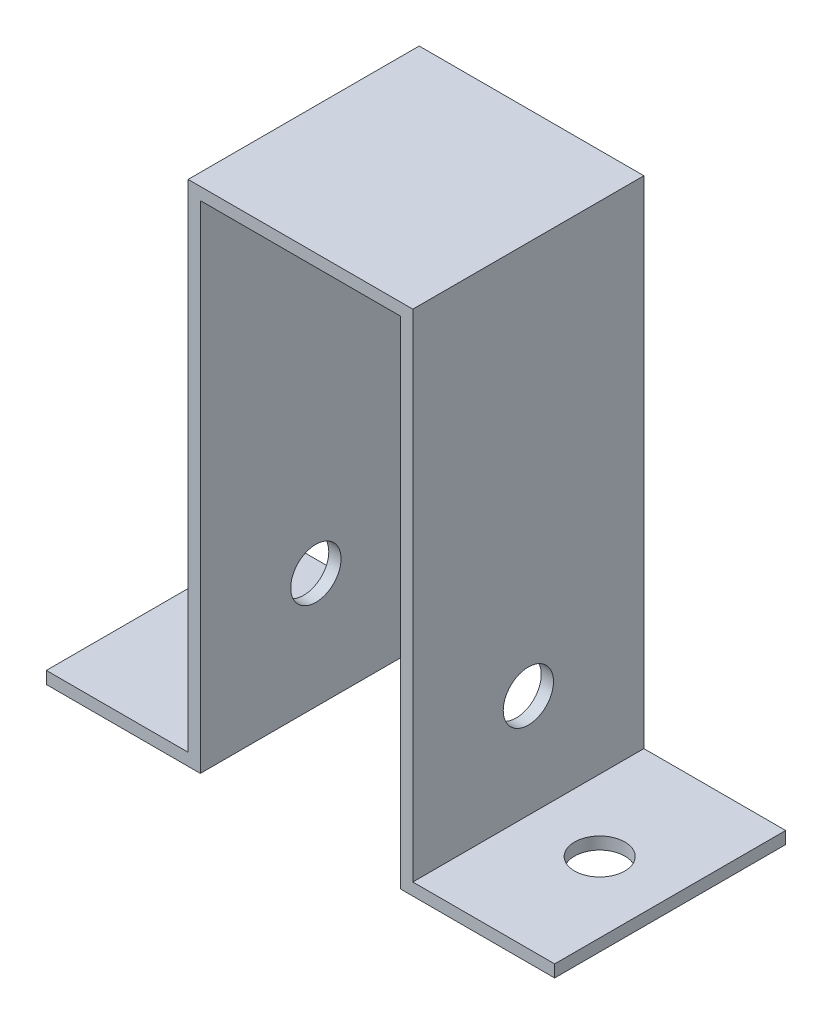
SolidWorks part; units mm, degrees
ref_plane "Front Plane" through (0, 0, 0) normal (0, 0, 1) x (1, 0, 0)
ref_plane "Top Plane" through (0, 0, 0) normal (0, 1, 0) x (1, 0, 0)
ref_plane "Right Plane" through (0, 0, 0) normal (1, 0, 0) x (0, 0, -1)
sketch "Sketch1" plane through (0, 0, 0) normal (0, 0, 1) x (1, 0, 0)
  line L0 (0, 32.2063) -> (-6.5, 32.2063)
  line L1 (-6.5, 32.2063) -> (-6.5, 0)
  line L2 (-6.5, 0) -> (-16.5, 0)
  line L3 (0, 33) -> (-7.2938, 33)
  line L4 (-7.2938, 33) -> (-7.2937, 0.7937)
  line L5 (-7.2937, 0.7937) -> (-16.5, 0.7937)
  line L6 (0, 33) -> (0, 32.2063)
  line L7 (-16.5, 0.7937) -> (-16.5, 0)
  dimension "D1" = 0.7937
  dimension "D2" = 6.5
  dimension "D3" = 33
  dimension "D4" = 10
extrude "Boss-Extrude1" add sketch "Sketch1" along normal mid plane 15
hole_wizard "#4 Clearance Hole1" positions "Sketch3" profile "Sketch2" hole size "#4" standard "ANSI Inch" end condition through all
sketch "Sketch3" plane through (-6.5, 0, 0) normal (1, 0, 0) x (0, 0, -1)
  line L1 (0, 0) -> (0, 28.3286) construction
  line L2 (-7.5, 0) -> (7.5, 0) construction
  point P0 (0, 7.5)
  dimension "D1" = 7.5
sketch "Sketch2" plane through (-6.5, 7.5, 0) normal (0, 1, 0) x (0, 0, -1)
  line L0 (0, 0) -> (0, 10)
  line L1 (0, 10) -> (1.6319, 10)
  line L2 (1.6319, 10) -> (1.6319, 0)
  line L5 (1.6319, 0) -> (0, 0)
  line L11 (0, -6.35) -> (0, 107.95) construction
  dimension "Thru Hole Dia." = 3.2639
  dimension "Thru Hole Depth" = 10
mirror "Mirror1" about plane through (0, 0, 0) normal (1, 0, 0) of "#4 Clearance Hole1", "Boss-Extrude1"
hole_wizard "#4 Clearance Hole2" positions "Sketch7" profile "Sketch6" hole size "#4" standard "ANSI Inch" end condition through all
sketch "Sketch7" plane through (0, 0, 0) normal (0, -1, 0) x (-1, 0, 0)
  line L0 (16.5, 0) -> (-16.5, 0) construction
  line L1 (16.5, -7.5) -> (16.5, 7.5) construction
  line L2 (-16.5, -7.5) -> (-16.5, 7.5) construction
  line L4 (0, -9.0859) -> (0, 11.9056) construction
  point P0 (11.925, 0)
  point P19 (-11.925, 0)
  dimension "D1" = 11.925
sketch "Sketch6" plane through (-11.925, 0, 0) normal (1, 0, 0) x (0, 0, -1)
  line L0 (0, 0) -> (0, 33)
  line L1 (0, 33) -> (1.6319, 33)
  line L2 (1.6319, 33) -> (1.6319, 0)
  line L5 (1.6319, 0) -> (0, 0)
  line L11 (0, -6.35) -> (0, 107.95) construction
  dimension "Thru Hole Dia." = 3.2639
  dimension "Thru Hole Depth" = 33
